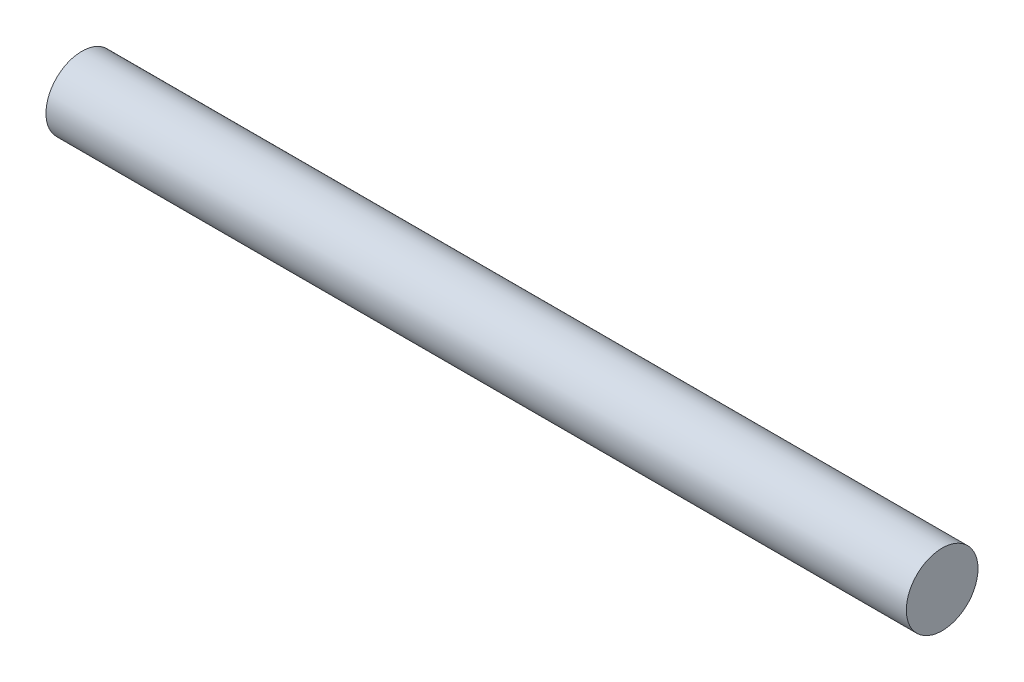
SolidWorks part; units mm, degrees
material "AISI 304"
ref_plane "前视基准面" through (0, 0, 0) normal (0, 0, 1) x (1, 0, 0)
ref_plane "上视基准面" through (0, 0, 0) normal (0, 1, 0) x (1, 0, 0)
ref_plane "右视基准面" through (0, 0, 0) normal (1, 0, 0) x (0, 0, -1)
sketch "Sketch1" plane through (0, 0, 0) normal (1, 0, 0) x (0, 0, -1)
  circle A0 centre (0, 0) radius 5
  dimension "D1" = 10
extrude "Boss-Extrude1" add sketch "Sketch1" along normal blind 120
